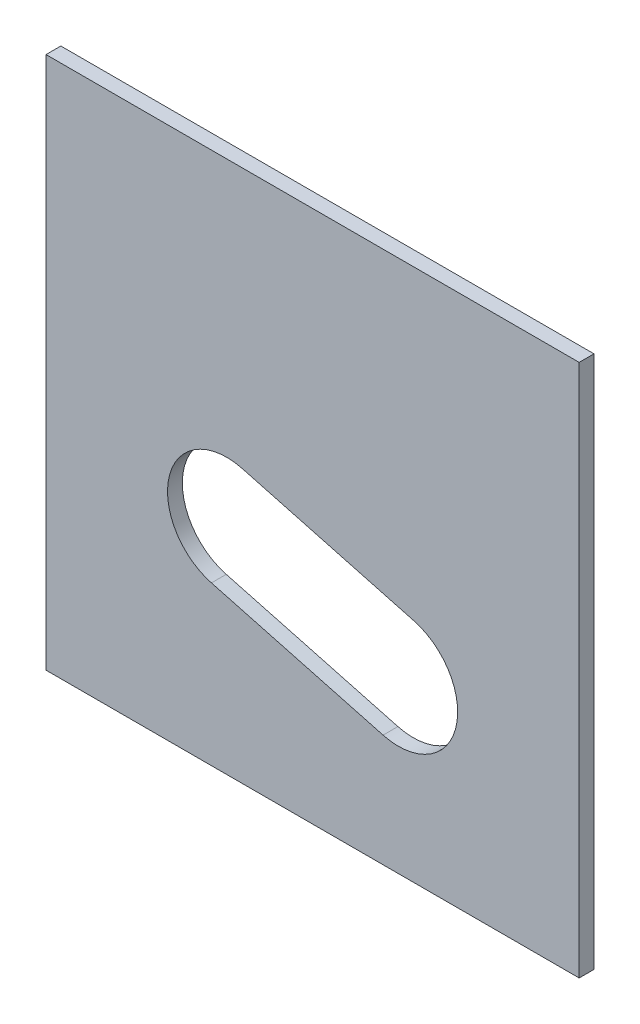
SolidWorks part; units mm, degrees
material "Thornel Mat VMA"
ref_plane "Front Plane" through (0, 0, 0) normal (0, 0, 1) x (1, 0, 0)
ref_plane "Top Plane" through (0, 0, 0) normal (0, 1, 0) x (1, 0, 0)
ref_plane "Right Plane" through (0, 0, 0) normal (1, 0, 0) x (0, 0, -1)
sketch "Sketch1" plane through (0, 0, 0) normal (0, 0, 1) x (1, 0, 0)
  line L1 (-90, -90) -> (90, -90)
  line L2 (-90, -90) -> (-90, 90)
  line L3 (-90, 90) -> (90, 90)
  line L4 (90, -90) -> (90, 90)
  line L5 (-90, -90) -> (90, 90) construction
  line L6 (-90, 90) -> (90, -90) construction
  point P0 (0, 0)
  dimension "D1" = 180
  dimension "D2" = 180
extrude "Boss-Extrude1" add sketch "Sketch1" along normal blind 5
sketch "Sketch2" plane through (0, 0, 0) normal (0, 0, -1) x (-1, 0, 0)
  line L0 (-90, 40) -> (-9.8, 90)
  line L1 (-90, -90) -> (-90, 90) construction
  line L2 (-90, 90) -> (90, 90) construction
  line L3 (-9.8, 90) -> (-90, 90)
  line L4 (-90, 90) -> (-90, 40)
  dimension "D1" = 50
  dimension "D2" = 80.2
sketch "Sketch3" plane through (0, 0, 0) normal (0, 0, -1) x (-1, 0, 0)
  line L0 (-28.9778, -32.7646) -> (28.9778, -17.2354) construction
  line L1 (-34.1542, -13.4461) -> (23.8014, 2.0831)
  line L2 (-23.8014, -52.0831) -> (34.1542, -36.5539)
  line L3 (90, -90) -> (-90, -90) construction
  arc A0 (-34.1542, -13.4461) -> (-23.8014, -52.0831) centre (-28.9778, -32.7646) ccw
  arc A1 (34.1542, -36.5539) -> (23.8014, 2.0831) centre (28.9778, -17.2354) ccw
  point P2 (0, -25)
  point P9 (0, 0)
  dimension "D4" = 20
  dimension "D1" = 15
  dimension "D2" = 25
  dimension "D3" = 60
extrude "Cut-Extrude1" cut sketch "Sketch3" against normal through all
